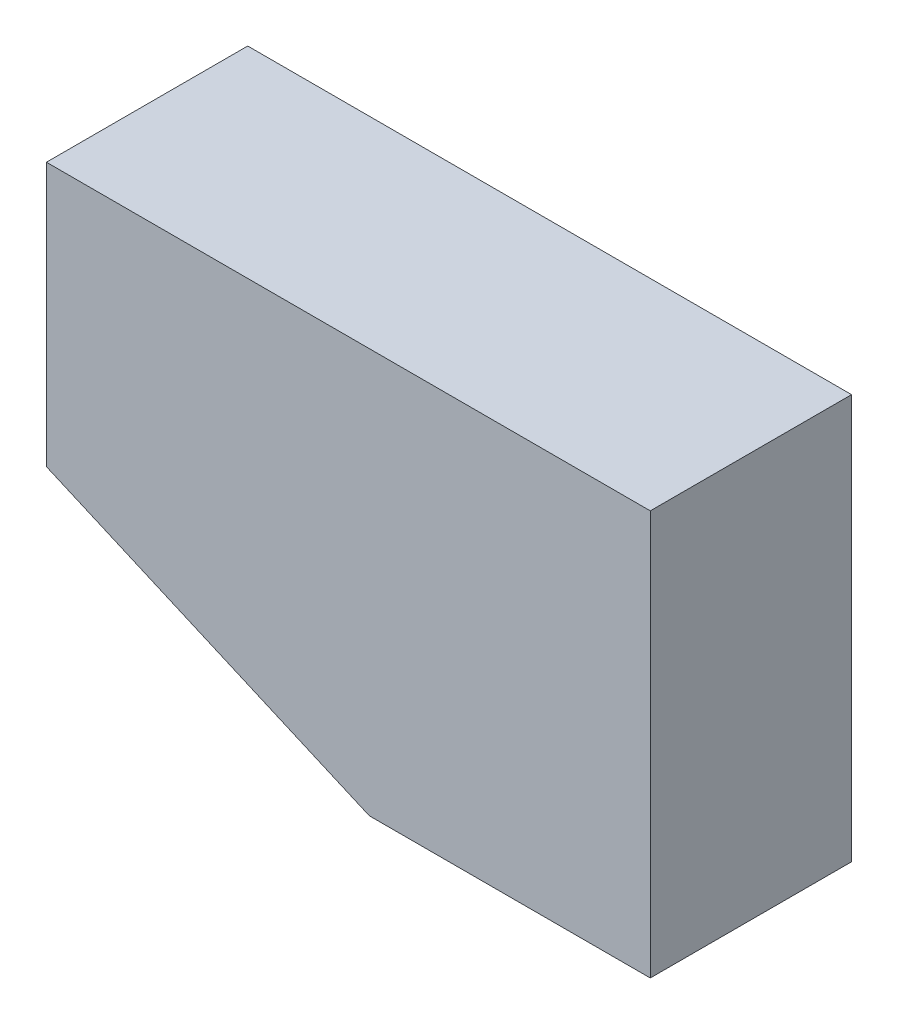
SolidWorks part; units mm, degrees
material "Cedar"
ref_plane "Front Plane" through (0, 0, 0) normal (0, 0, 1) x (1, 0, 0)
ref_plane "Top Plane" through (0, 0, 0) normal (0, 1, 0) x (1, 0, 0)
ref_plane "Right Plane" through (0, 0, 0) normal (1, 0, 0) x (0, 0, -1)
sketch "Sketch3" plane through (0, 0, 0) normal (0, 0, 1) x (1, 0, 0)
  line L0 (9.153, -66.6667) -> (329.9333, -206.6667)
  line L1 (9.153, 193.3333) -> (609.153, 193.3333)
  line L2 (9.153, 193.3333) -> (9.153, -66.6667)
  line L3 (329.9333, -206.6667) -> (609.153, -206.6667)
  line L4 (609.153, 193.3333) -> (609.153, -206.6667)
  dimension "D1" = 400
  dimension "D2" = 600
  dimension "D3" = 260
  dimension "D4" = 350
extrude "Boss-Extrude1" add sketch "Sketch3" along normal blind 200
shell "Shell1" thickness 6
sketch "Sketch4" plane through (0, 193.3333, 0) normal (0, 1, 0) x (1, 0, 0)
  line L1 (9.153, 0) -> (609.153, 0)
  line L2 (9.153, 0) -> (9.153, -200)
  line L3 (9.153, -200) -> (609.153, -200)
  line L4 (609.153, 0) -> (609.153, -200)
extrude "Boss-Extrude2" add sketch "Sketch4" along normal blind 2
